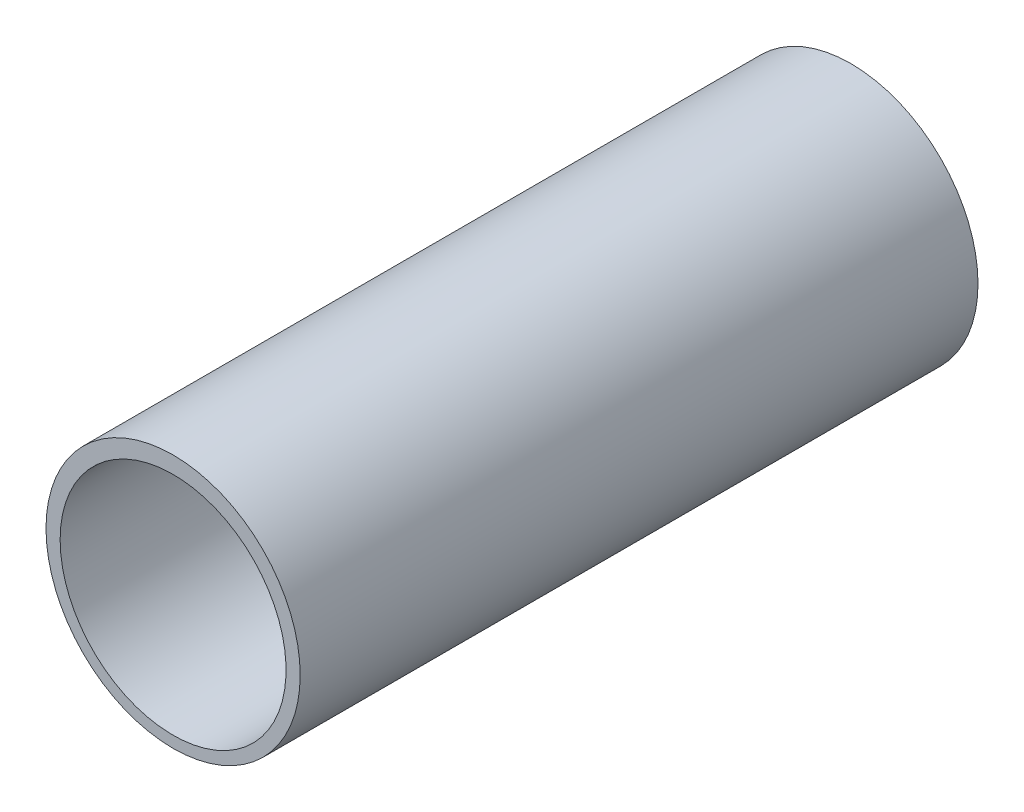
SolidWorks part; units mm, degrees
ref_plane "Front Plane" through (0, 0, 0) normal (0, 0, 1) x (1, 0, 0)
ref_plane "Top Plane" through (0, 0, 0) normal (0, 1, 0) x (1, 0, 0)
ref_plane "Right Plane" through (0, 0, 0) normal (1, 0, 0) x (0, 0, -1)
sketch "Sketch5" plane through (0, 0, 0) normal (0, 0, 1) x (1, 0, 0)
  circle A0 centre (0, 0) radius 57.15
  dimension "D1" = 114.3
extrude "Boss-Extrude5" add sketch "Sketch5" along normal blind 304.8 contours A0
sketch "Sketch7" plane through (0, 0, 0) normal (0, 0, -1) x (-1, 0, 0)
  circle A0 centre (0, -1.2248) radius 50.8
  dimension "D1" = 101.6
extrude "Cut-Extrude5" cut sketch "Sketch7" against normal through all both
